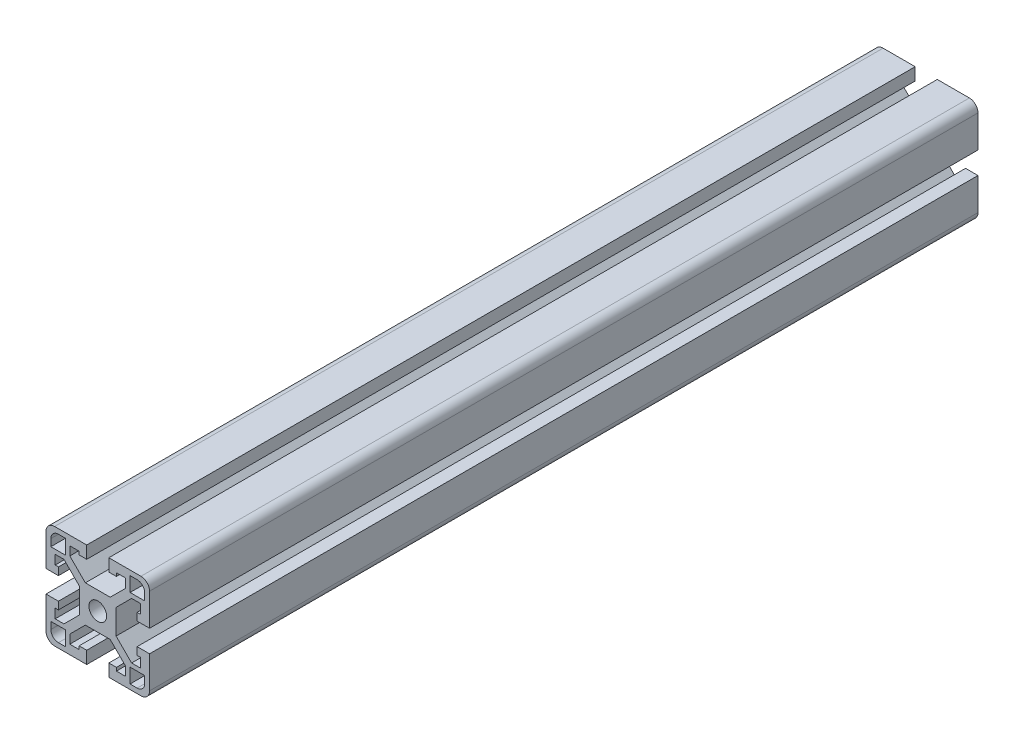
SolidWorks part; units mm, degrees
ref_plane "Front Plane" through (0, 0, 0) normal (0, 0, 1) x (1, 0, 0)
ref_plane "Top Plane" through (0, 0, 0) normal (0, 1, 0) x (1, 0, 0)
ref_plane "Right Plane" through (0, 0, 0) normal (1, 0, 0) x (0, 0, -1)
sketch "Sketch1" plane through (0, 0, 0) normal (0, 0, 1) x (1, 0, 0)
  line L0 (-11.8872, 17.272) -> (-14.478, 17.272)
  line L1 (-11.8872, 11.8872) -> (-11.8872, 17.272)
  line L2 (-17.272, 11.8872) -> (-11.8872, 11.8872)
  line L3 (-17.272, 14.478) -> (-17.272, 11.8872)
  line L4 (14.478, 17.272) -> (11.8872, 17.272)
  line L5 (17.272, 11.8872) -> (17.272, 14.478)
  line L6 (11.8872, 11.8872) -> (17.272, 11.8872)
  line L7 (11.8872, 17.272) -> (11.8872, 11.8872)
  line L8 (11.8872, -17.272) -> (14.478, -17.272)
  line L9 (11.8872, -11.8872) -> (11.8872, -17.272)
  line L10 (17.272, -11.8872) -> (11.8872, -11.8872)
  line L11 (17.272, -14.478) -> (17.272, -11.8872)
  line L12 (-14.478, -17.272) -> (-11.8872, -17.272)
  line L13 (-17.272, -11.8872) -> (-17.272, -14.478)
  line L14 (-11.8872, -11.8872) -> (-17.272, -11.8872)
  line L15 (-11.8872, -17.272) -> (-11.8872, -11.8872)
  line L16 (-6.731, 4.5757) -> (-6.731, -4.5757)
  line L17 (-6.731, -4.5757) -> (-12.4423, -10.287)
  line L18 (-12.4423, -10.287) -> (-15.6718, -10.287)
  line L19 (-15.6718, -10.287) -> (-15.6718, -6.858)
  line L20 (-15.6718, -6.858) -> (-14.478, -6.858)
  line L21 (-14.478, -6.858) -> (-14.478, -4.064)
  line L22 (-14.478, -4.064) -> (-19.05, -4.064)
  line L23 (-19.05, -4.064) -> (-19.05, -15.875)
  line L24 (-15.875, -19.05) -> (-4.064, -19.05)
  line L25 (-4.064, -19.05) -> (-4.064, -14.478)
  line L26 (-4.064, -14.478) -> (-6.858, -14.478)
  line L27 (-6.858, -14.478) -> (-6.858, -15.6718)
  line L28 (-6.858, -15.6718) -> (-10.287, -15.6718)
  line L29 (-10.287, -15.6718) -> (-10.287, -12.4423)
  line L30 (-10.287, -12.4423) -> (-4.5757, -6.731)
  line L31 (-4.5757, -6.731) -> (4.5757, -6.731)
  line L32 (4.5757, -6.731) -> (10.287, -12.4423)
  line L33 (10.287, -12.4423) -> (10.287, -15.6718)
  line L34 (10.287, -15.6718) -> (6.858, -15.6718)
  line L35 (6.858, -15.6718) -> (6.858, -14.478)
  line L36 (6.858, -14.478) -> (4.064, -14.478)
  line L37 (4.064, -14.478) -> (4.064, -19.05)
  line L38 (4.064, -19.05) -> (15.875, -19.05)
  line L39 (19.05, -15.875) -> (19.05, -4.064)
  line L40 (19.05, -4.064) -> (14.478, -4.064)
  line L41 (14.478, -4.064) -> (14.478, -6.858)
  line L42 (14.478, -6.858) -> (15.6718, -6.858)
  line L43 (15.6718, -6.858) -> (15.6718, -10.287)
  line L44 (15.6718, -10.287) -> (12.4423, -10.287)
  line L45 (12.4423, -10.287) -> (6.731, -4.5757)
  line L46 (6.731, -4.5757) -> (6.731, 4.5757)
  line L47 (6.731, 4.5757) -> (12.4423, 10.287)
  line L48 (12.4423, 10.287) -> (15.6718, 10.287)
  line L49 (15.6718, 10.287) -> (15.6718, 6.858)
  line L50 (15.6718, 6.858) -> (14.478, 6.858)
  line L51 (14.478, 6.858) -> (14.478, 4.064)
  line L52 (14.478, 4.064) -> (19.05, 4.064)
  line L53 (19.05, 4.064) -> (19.05, 15.875)
  line L54 (15.875, 19.05) -> (4.064, 19.05)
  line L55 (4.064, 19.05) -> (4.064, 14.478)
  line L56 (4.064, 14.478) -> (6.858, 14.478)
  line L57 (6.858, 14.478) -> (6.858, 15.6718)
  line L58 (6.858, 15.6718) -> (10.287, 15.6718)
  line L59 (10.287, 15.6718) -> (10.287, 12.4423)
  line L60 (10.287, 12.4423) -> (4.5757, 6.731)
  line L61 (4.5757, 6.731) -> (-4.5757, 6.731)
  line L62 (-4.5757, 6.731) -> (-10.287, 12.4423)
  line L63 (-10.287, 12.4423) -> (-10.287, 15.6718)
  line L64 (-10.287, 15.6718) -> (-6.858, 15.6718)
  line L65 (-6.858, 15.6718) -> (-6.858, 14.478)
  line L66 (-6.858, 14.478) -> (-4.064, 14.478)
  line L67 (-4.064, 14.478) -> (-4.064, 19.05)
  line L68 (-4.064, 19.05) -> (-15.875, 19.05)
  line L69 (-19.05, 15.875) -> (-19.05, 4.064)
  line L70 (-19.05, 4.064) -> (-14.478, 4.064)
  line L71 (-14.478, 4.064) -> (-14.478, 6.858)
  line L72 (-14.478, 6.858) -> (-15.6718, 6.858)
  line L73 (-15.6718, 6.858) -> (-15.6718, 10.287)
  line L74 (-15.6718, 10.287) -> (-12.4423, 10.287)
  line L75 (-12.4423, 10.287) -> (-6.731, 4.5757)
  circle A0 centre (0, 0) radius 3.2639
  arc A1 (-19.05, -15.875) -> (-15.875, -19.05) centre (-15.875, -15.875) ccw
  arc A2 (15.875, -19.05) -> (19.05, -15.875) centre (15.875, -15.875) ccw
  arc A3 (19.05, 15.875) -> (15.875, 19.05) centre (15.875, 15.875) ccw
  arc A4 (-15.875, 19.05) -> (-19.05, 15.875) centre (-15.875, 15.875) ccw
  arc A5 (-14.478, 17.272) -> (-17.272, 14.478) centre (-14.478, 14.478) ccw
  arc A6 (17.272, 14.478) -> (14.478, 17.272) centre (14.478, 14.478) ccw
  arc A7 (14.478, -17.272) -> (17.272, -14.478) centre (14.478, -14.478) ccw
  arc A8 (-17.272, -14.478) -> (-14.478, -17.272) centre (-14.478, -14.478) ccw
extrude "Boss-Extrude1" add sketch "Sketch1" along normal mid plane 304.8
